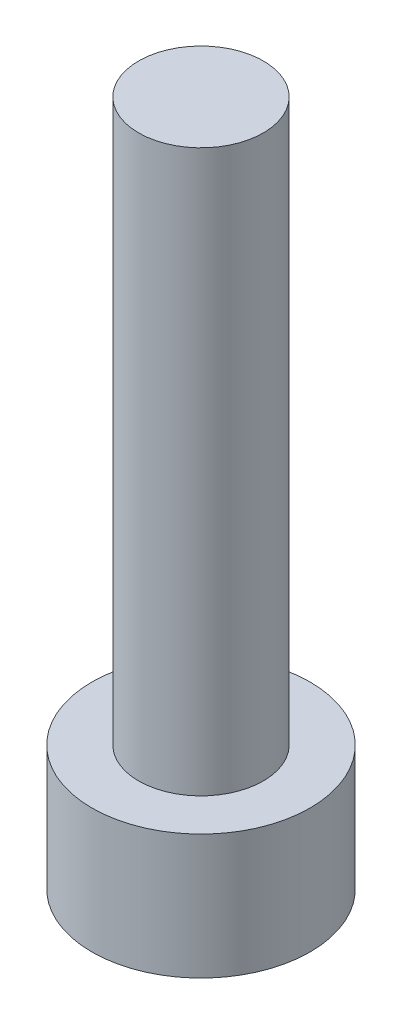
SolidWorks part; units mm, degrees
ref_plane "前视基准面" through (0, 0, 0) normal (0, 0, 1) x (1, 0, 0)
ref_plane "上视基准面" through (0, 0, 0) normal (0, 1, 0) x (1, 0, 0)
ref_plane "右视基准面" through (0, 0, 0) normal (1, 0, 0) x (0, 0, -1)
other "Configuration Table"
sketch "草图1" plane through (0, 0, 0) normal (0, 1, 0) x (1, 0, 0)
  circle A0 centre (0, 0) radius 3.5
  dimension "D1" = 7
extrude "凸台-拉伸1" add sketch "草图1" along normal blind 4
sketch "草图2" plane through (0, 4, 0) normal (0, 1, 0) x (1, 0, 0)
  circle A0 centre (0, 0) radius 2
  dimension "D1" = 4
extrude "凸台-拉伸2" add sketch "草图2" along normal blind 18
cosmetic thread "装饰螺纹线1" parameters "D1"=18, "D2"=3
sketch "草图3" plane through (0, 0, 0) normal (0, -1, 0) x (1, 0, 0)
  line L1 (1.2713, -1.1763) -> (1.6544, 0.5128)
  line L2 (1.6544, 0.5128) -> (0.3831, 1.6892)
  line L3 (0.3831, 1.6892) -> (-1.2713, 1.1763)
  line L4 (-1.2713, 1.1763) -> (-1.6544, -0.5128)
  line L5 (-1.6544, -0.5128) -> (-0.3831, -1.6892)
  line L6 (-0.3831, -1.6892) -> (1.2713, -1.1763)
  circle A0 centre (0, 0) radius 1.5 construction
  dimension "D1" = 3
extrude "切除-拉伸1" cut sketch "草图3" against normal blind 1.5
